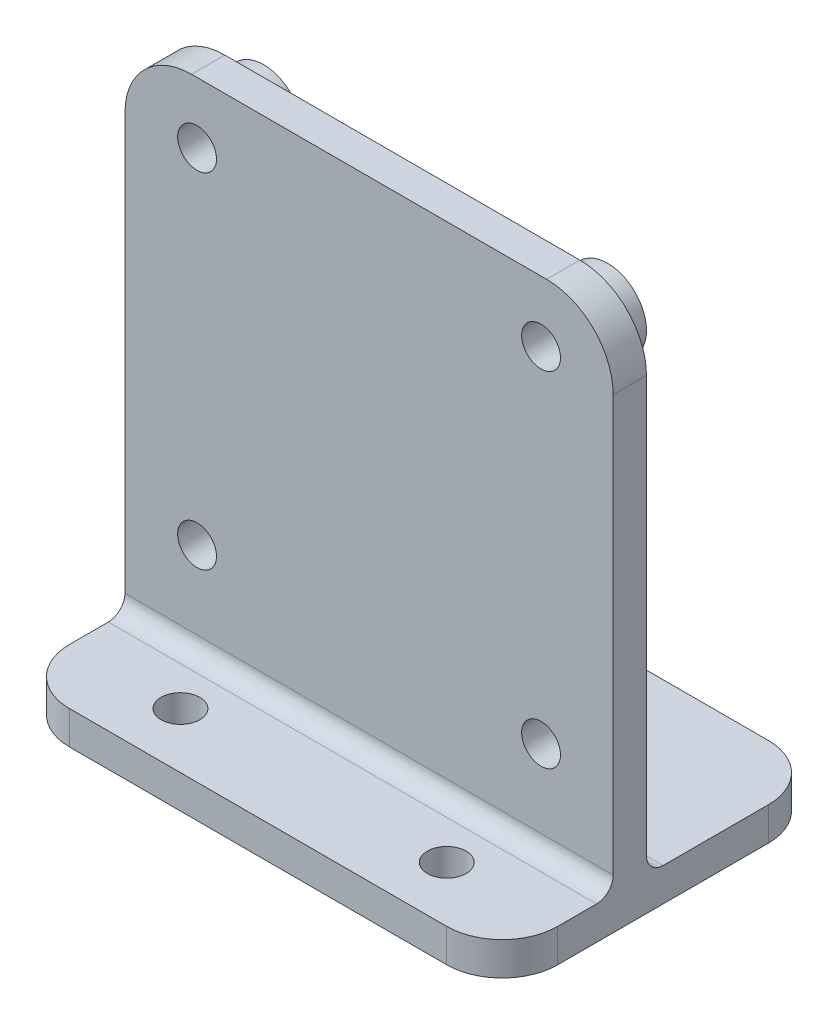
SolidWorks part; units mm, degrees
material "Acrílico (Impacto medio-alto)"
ref_plane "Alzado" through (0, 0, 0) normal (0, 0, 1) x (1, 0, 0)
ref_plane "Planta" through (0, 0, 0) normal (0, 1, 0) x (1, 0, 0)
ref_plane "Vista lateral" through (0, 0, 0) normal (1, 0, 0) x (0, 0, -1)
sketch "Croquis3" plane through (0, 0, 0) normal (1, 0, 0) x (0, 0, -1)
  line L1 (-11.5, 0) -> (-11.5, 3)
  line L2 (-11.5, 3) -> (-1.5, 3)
  line L3 (-1.5, 3) -> (-1.5, 48)
  line L4 (-1.5, 48) -> (1.5, 48)
  line L5 (1.5, 48) -> (1.5, 3)
  line L6 (1.5, 3) -> (17.5, 3)
  line L7 (17.5, 3) -> (17.5, 0)
  line L8 (0, 0) -> (17.5, 0)
  line L9 (0, 0) -> (-11.5, 0)
  point P4 (0, 0)
  point P11 (0, 48)
  dimension "D1" = 3
  dimension "D2" = 3
  dimension "D3" = 3
  dimension "D4" = 16
  dimension "D5" = 45
  dimension "D6" = 10
extrude "Saliente-Extruir1" add sketch "Croquis3" along normal mid plane 44
sketch "Croquis4" plane through (0, 0, -1.5) normal (0, 0, -1) x (-1, 0, 0)
  circle A0 centre (15.5, 42.5) radius 1.75
  circle A1 centre (-15.5, 11.5) radius 1.75
  dimension "D1" = 3.5
extrude "Cortar-Extruir1" cut sketch "Croquis4" against normal through all
mirror "Simetría1" about plane through (0, 0, 0) normal (1, 0, 0) of "Cortar-Extruir1"
sketch "Croquis5" plane through (0, 3, 0) normal (0, 1, 0) x (1, 0, 0)
  line L2 (-22, -1.5) -> (-22, -11.5) construction
  line L3 (22, -1.5) -> (22, -11.5) construction
  circle A0 centre (-12, -6.5) radius 1.75
  circle A1 centre (12, -6.5) radius 1.75
  point P6 (-22, -6.5)
  dimension "D1" = 3.5
  dimension "D2" = 10
  dimension "D3" = 10
extrude "Cortar-Extruir2" cut sketch "Croquis5" against normal through all
fillet "Redondeo1" radius 6 2 edges at (-22, 48, 0) (22, 48, 0)
fillet "Redondeo2" radius 5 4 edges at (22, 1.5, -17.5) (-22, 1.5, -17.5) (-22, 1.5, 11.5) (22, 1.5, 11.5)
fillet "Redondeo3" radius 1.5 2 edges at (0, 3, 1.5) (0, 3, -1.5)
sketch "Croquis6" plane through (0, 0, -1.5) normal (0, 0, -1) x (-1, 0, 0)
  circle A0 centre (-15.5, 42.5) radius 1.75 construction
  circle A1 centre (-15.5, 42.5) radius 1.75
  circle A2 centre (-15.5, 42.5) radius 3.5
  circle A3 centre (-15.5, 11.5) radius 1.75 construction
  circle A4 centre (-15.5, 11.5) radius 1.75
  circle A5 centre (-15.5, 11.5) radius 3.5
  dimension "D1" = 7
extrude "Saliente-Extruir2" add sketch "Croquis6" along normal blind 3
mirror "Simetría2" about plane through (0, 0, 0) normal (1, 0, 0) of "Saliente-Extruir2"
